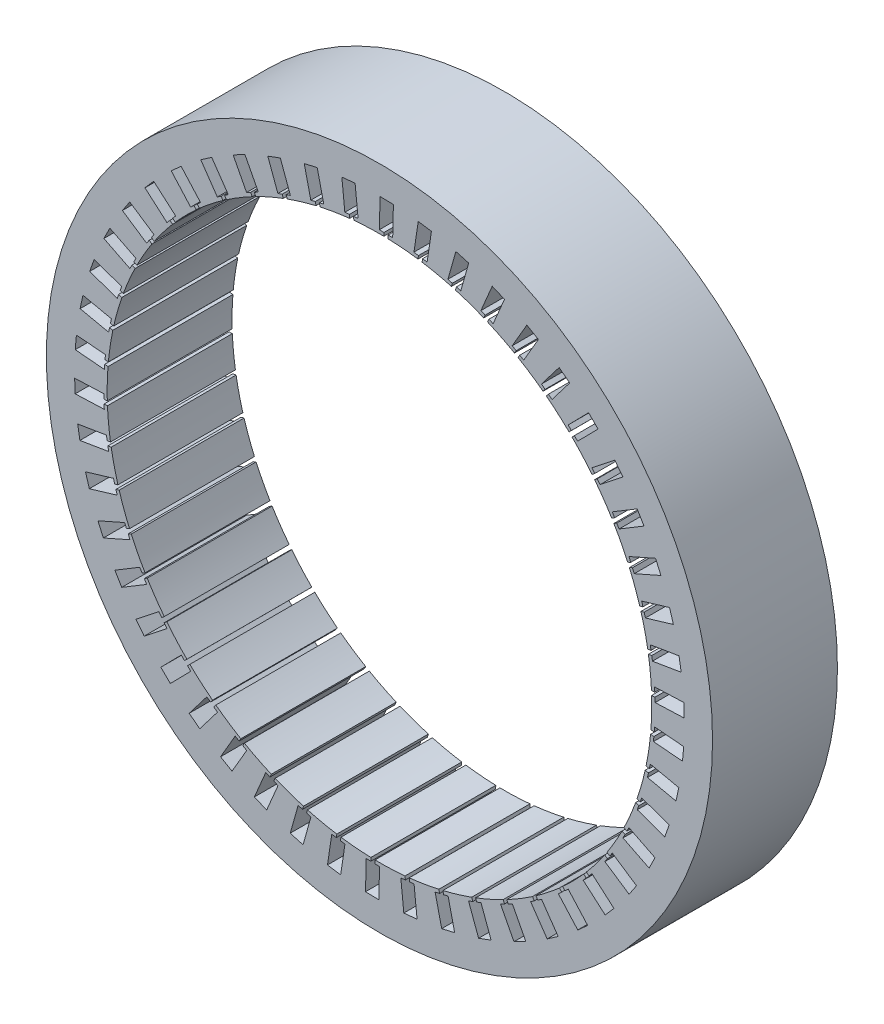
SolidWorks part; units mm, degrees
ref_plane "Спереди" through (0, 0, 0) normal (0, 0, 1) x (1, 0, 0)
ref_plane "Сверху" through (0, 0, 0) normal (0, 1, 0) x (1, 0, 0)
ref_plane "Справа" through (0, 0, 0) normal (1, 0, 0) x (0, 0, -1)
sketch "Эскиз1" plane through (0, 0, 0) normal (0, 0, 1) x (1, 0, 0)
  circle A0 centre (0, 0) radius 80
  circle A1 centre (0, 0) radius 65.4
extrude "Rotor_stack" add sketch "Эскиз1" along normal blind 30 from offset 15
sketch "Эскиз2" plane through (0, 0, 0) normal (0, 0, 1) x (1, 0, 0)
  line L0 (64.5685, 2.0162) -> (66.1692, 2.0786)
  line L1 (66.1692, 2.0786) -> (66.2121, 0.9794)
  line L2 (66.2121, 0.9794) -> (73.2068, 1.2521)
  line L3 (73.2068, 1.2521) -> (73.0822, 4.4496)
  line L4 (73.0822, 4.4496) -> (66.0875, 4.177)
  line L5 (66.0875, 4.177) -> (66.1303, 3.0778)
  line L6 (66.1303, 3.0778) -> (64.5296, 3.0155)
  line L7 (64.5296, 3.0155) -> (64.5685, 2.0162)
  line L8 (63.8067, 10.0929) -> (65.387, 10.3554)
  line L9 (65.387, 10.3554) -> (65.5672, 9.2703)
  line L10 (65.5672, 9.2703) -> (72.4726, 10.4174)
  line L11 (72.4726, 10.4174) -> (71.9482, 13.5742)
  line L12 (71.9482, 13.5742) -> (65.0428, 12.427)
  line L13 (65.0428, 12.427) -> (65.2231, 11.3419)
  line L14 (65.2231, 11.3419) -> (63.6428, 11.0794)
  line L15 (63.6428, 11.0794) -> (63.8067, 10.0929)
  line L16 (62.0386, 18.0104) -> (63.5735, 18.4689)
  line L17 (63.5735, 18.4689) -> (63.8883, 17.4149)
  line L18 (63.8883, 17.4149) -> (70.5955, 19.4185)
  line L19 (70.5955, 19.4185) -> (69.6796, 22.4846)
  line L20 (69.6796, 22.4846) -> (62.9724, 20.4811)
  line L21 (62.9724, 20.4811) -> (63.2873, 19.4271)
  line L22 (63.2873, 19.4271) -> (61.7524, 18.9686)
  line L23 (61.7524, 18.9686) -> (62.0386, 18.0104)
  line L24 (59.2921, 25.6439) -> (60.7574, 26.2912)
  line L25 (60.7574, 26.2912) -> (61.2019, 25.2849)
  line L26 (61.2019, 25.2849) -> (67.605, 28.1133)
  line L27 (67.605, 28.1133) -> (66.312, 31.0405)
  line L28 (66.312, 31.0405) -> (59.9089, 28.2121)
  line L29 (59.9089, 28.2121) -> (60.3534, 27.2059)
  line L30 (60.3534, 27.2059) -> (58.888, 26.5586)
  line L31 (58.888, 26.5586) -> (59.2921, 25.6439)
  line L32 (55.6105, 32.8729) -> (56.9832, 33.6988)
  line L33 (56.9832, 33.6988) -> (57.5503, 32.7562)
  line L34 (57.5503, 32.7562) -> (63.5484, 36.3648)
  line L35 (63.5484, 36.3648) -> (61.8988, 39.1068)
  line L36 (61.8988, 39.1068) -> (55.9006, 35.4982)
  line L37 (55.9006, 35.4982) -> (56.4677, 34.5556)
  line L38 (56.4677, 34.5556) -> (55.095, 33.7298)
  line L39 (55.095, 33.7298) -> (55.6105, 32.8729)
  line L40 (51.0519, 39.5836) -> (52.3103, 40.5749)
  line L41 (52.3103, 40.5749) -> (52.991, 39.7109)
  line L42 (52.991, 39.7109) -> (58.4896, 44.0428)
  line L43 (58.4896, 44.0428) -> (56.5093, 46.5564)
  line L44 (56.5093, 46.5564) -> (51.0107, 42.2245)
  line L45 (51.0107, 42.2245) -> (51.6914, 41.3604)
  line L46 (51.6914, 41.3604) -> (50.4331, 40.3691)
  line L47 (50.4331, 40.3691) -> (51.0519, 39.5836)
  line L48 (45.6882, 45.67) -> (46.8124, 46.8112)
  line L49 (46.8124, 46.8112) -> (47.5961, 46.0393)
  line L50 (47.5961, 46.0393) -> (52.5084, 51.0262)
  line L51 (52.5084, 51.0262) -> (50.2286, 53.2718)
  line L52 (50.2286, 53.2718) -> (45.3163, 48.2849)
  line L53 (45.3163, 48.2849) -> (46.1, 47.513)
  line L54 (46.1, 47.513) -> (44.9758, 46.3717)
  line L55 (44.9758, 46.3717) -> (45.6882, 45.67)
  line L56 (39.604, 51.0361) -> (40.5763, 52.3092)
  line L57 (40.5763, 52.3092) -> (41.4505, 51.6416)
  line L58 (41.4505, 51.6416) -> (45.699, 57.2049)
  line L59 (45.699, 57.2049) -> (43.1558, 59.1471)
  line L60 (43.1558, 59.1471) -> (38.9073, 53.5838)
  line L61 (38.9073, 53.5838) -> (39.7815, 52.9162)
  line L62 (39.7815, 52.9162) -> (38.8093, 51.643)
  line L63 (38.8093, 51.643) -> (39.604, 51.0361)
  line L64 (32.8952, 55.5974) -> (33.7002, 56.9823)
  line L65 (33.7002, 56.9823) -> (34.6512, 56.4295)
  line L66 (34.6512, 56.4295) -> (38.169, 62.4814)
  line L67 (38.169, 62.4814) -> (35.4024, 64.0895)
  line L68 (35.4024, 64.0895) -> (31.8847, 58.0376)
  line L69 (31.8847, 58.0376) -> (32.8357, 57.4848)
  line L70 (32.8357, 57.4848) -> (32.0307, 56.0999)
  line L71 (32.0307, 56.0999) -> (32.8952, 55.5974)
  line L72 (25.6676, 59.2818) -> (26.2927, 60.7567)
  line L73 (26.2927, 60.7567) -> (27.3055, 60.3275)
  line L74 (27.3055, 60.3275) -> (30.037, 66.7726)
  line L75 (30.037, 66.7726) -> (27.0907, 68.0213)
  line L76 (27.0907, 68.0213) -> (24.3592, 61.5762)
  line L77 (24.3592, 61.5762) -> (25.372, 61.147)
  line L78 (25.372, 61.147) -> (24.7469, 59.672)
  line L79 (24.7469, 59.672) -> (25.6676, 59.2818)
  line L80 (18.0352, 62.0314) -> (18.4706, 63.573)
  line L81 (18.4706, 63.573) -> (19.5292, 63.2741)
  line L82 (19.5292, 63.2741) -> (21.4314, 70.0107)
  line L83 (21.4314, 70.0107) -> (18.3518, 70.8803)
  line L84 (18.3518, 70.8803) -> (16.4496, 64.1437)
  line L85 (16.4496, 64.1437) -> (17.5082, 63.8448)
  line L86 (17.5082, 63.8448) -> (17.0729, 62.3031)
  line L87 (17.0729, 62.3031) -> (18.0352, 62.0314)
  line L88 (10.1184, 63.8026) -> (10.3571, 65.3867)
  line L89 (10.3571, 65.3867) -> (11.4448, 65.2228)
  line L90 (11.4448, 65.2228) -> (12.4877, 72.1447)
  line L91 (12.4877, 72.1447) -> (9.3234, 72.6214)
  line L92 (9.3234, 72.6214) -> (8.2805, 65.6996)
  line L93 (8.2805, 65.6996) -> (9.3683, 65.5357)
  line L94 (9.3683, 65.5357) -> (9.1296, 63.9516)
  line L95 (9.1296, 63.9516) -> (10.1184, 63.8026)
  line L96 (2.0421, 64.5677) -> (2.0803, 66.1692)
  line L97 (2.0803, 66.1692) -> (3.18, 66.1429)
  line L98 (3.18, 66.1429) -> (3.3471, 73.1409)
  line L99 (3.3471, 73.1409) -> (0.148, 73.2173)
  line L100 (0.148, 73.2173) -> (-0.0191, 66.2193)
  line L101 (-0.0191, 66.2193) -> (1.0806, 66.1931)
  line L102 (1.0806, 66.1931) -> (1.0423, 64.5916)
  line L103 (1.0423, 64.5916) -> (2.0421, 64.5677)
  line L104 (-6.0665, 64.3145) -> (-6.2293, 65.9082)
  line L105 (-6.2293, 65.9082) -> (-5.135, 66.0199)
  line L106 (-5.135, 66.0199) -> (-5.8463, 72.9837)
  line L107 (-5.8463, 72.9837) -> (-9.0297, 72.6585)
  line L108 (-9.0297, 72.6585) -> (-8.3184, 65.6948)
  line L109 (-8.3184, 65.6948) -> (-7.2241, 65.8066)
  line L110 (-7.2241, 65.8066) -> (-7.0613, 64.2129)
  line L111 (-7.0613, 64.2129) -> (-6.0665, 64.3145)
  line L112 (-14.0794, 63.047) -> (-14.4407, 64.6077)
  line L113 (-14.4407, 64.6077) -> (-13.369, 64.8558)
  line L114 (-13.369, 64.8558) -> (-14.9475, 71.6755)
  line L115 (-14.9475, 71.6755) -> (-18.065, 70.9539)
  line L116 (-18.065, 70.9539) -> (-16.4866, 64.1342)
  line L117 (-16.4866, 64.1342) -> (-15.4149, 64.3822)
  line L118 (-15.4149, 64.3822) -> (-15.0537, 62.8215)
  line L119 (-15.0537, 62.8215) -> (-14.0794, 63.047)
  line L120 (-21.8703, 60.7853) -> (-22.4243, 62.2884)
  line L121 (-22.4243, 62.2884) -> (-21.3922, 62.6688)
  line L122 (-21.3922, 62.6688) -> (-23.8129, 69.2369)
  line L123 (-23.8129, 69.2369) -> (-26.8155, 68.1302)
  line L124 (-26.8155, 68.1302) -> (-24.3947, 61.5621)
  line L125 (-24.3947, 61.5621) -> (-23.3626, 61.9426)
  line L126 (-23.3626, 61.9426) -> (-22.8086, 60.4395)
  line L127 (-22.8086, 60.4395) -> (-21.8703, 60.7853)
  line L128 (-29.3163, 57.5649) -> (-30.0543, 58.9867)
  line L129 (-30.0543, 58.9867) -> (-29.078, 59.4935)
  line L130 (-29.078, 59.4935) -> (-32.3028, 65.7064)
  line L131 (-32.3028, 65.7064) -> (-35.143, 64.2321)
  line L132 (-35.143, 64.2321) -> (-31.9181, 58.0192)
  line L133 (-31.9181, 58.0192) -> (-30.9418, 58.526)
  line L134 (-30.9418, 58.526) -> (-30.2038, 57.1042)
  line L135 (-30.2038, 57.1042) -> (-29.3163, 57.5649)
  line L136 (-36.2999, 53.4367) -> (-37.2103, 54.7548)
  line L137 (-37.2103, 54.7548) -> (-36.3052, 55.3799)
  line L138 (-36.3052, 55.3799) -> (-40.2833, 61.1396)
  line L139 (-40.2833, 61.1396) -> (-42.9163, 59.3211)
  line L140 (-42.9163, 59.3211) -> (-38.9382, 53.5613)
  line L141 (-38.9382, 53.5613) -> (-38.0331, 54.1865)
  line L142 (-38.0331, 54.1865) -> (-37.1227, 52.8684)
  line L143 (-37.1227, 52.8684) -> (-36.2999, 53.4367)
  line L144 (-42.711, 48.4657) -> (-43.7795, 49.6593)
  line L145 (-43.7795, 49.6593) -> (-42.9598, 50.393)
  line L146 (-42.9598, 50.393) -> (-47.6285, 55.6087)
  line L147 (-47.6285, 55.6087) -> (-50.0128, 53.4745)
  line L148 (-50.0128, 53.4745) -> (-45.3442, 48.2587)
  line L149 (-45.3442, 48.2587) -> (-44.5246, 48.9924)
  line L150 (-44.5246, 48.9924) -> (-43.4561, 47.7988)
  line L151 (-43.4561, 47.7988) -> (-42.711, 48.4657)
  line L152 (-48.4486, 42.7304) -> (-49.6582, 43.7807)
  line L153 (-49.6582, 43.7807) -> (-48.937, 44.6113)
  line L154 (-48.937, 44.6113) -> (-54.2225, 49.2008)
  line L155 (-54.2225, 49.2008) -> (-56.3206, 46.7845)
  line L156 (-56.3206, 46.7845) -> (-51.035, 42.1951)
  line L157 (-51.035, 42.1951) -> (-50.3138, 43.0257)
  line L158 (-50.3138, 43.0257) -> (-49.1043, 41.9754)
  line L159 (-49.1043, 41.9754) -> (-48.4486, 42.7304)
  line L160 (-53.4221, 36.3213) -> (-54.7538, 37.2117)
  line L161 (-54.7538, 37.2117) -> (-54.1424, 38.1261)
  line L162 (-54.1424, 38.1261) -> (-59.9615, 42.0169)
  line L163 (-59.9615, 42.0169) -> (-61.7401, 39.3568)
  line L164 (-61.7401, 39.3568) -> (-55.9211, 35.466)
  line L165 (-55.9211, 35.466) -> (-55.3096, 36.3804)
  line L166 (-55.3096, 36.3804) -> (-53.978, 35.49)
  line L167 (-53.978, 35.49) -> (-53.4221, 36.3213)
  line L168 (-57.5531, 29.3393) -> (-58.9859, 30.0558)
  line L169 (-58.9859, 30.0558) -> (-58.4939, 31.0396)
  line L170 (-58.4939, 31.0396) -> (-64.7548, 34.1705)
  line L171 (-64.7548, 34.1705) -> (-66.186, 31.3084)
  line L172 (-66.186, 31.3084) -> (-59.9252, 28.1775)
  line L173 (-59.9252, 28.1775) -> (-59.4332, 29.1614)
  line L174 (-59.4332, 29.1614) -> (-58.0004, 28.4449)
  line L175 (-58.0004, 28.4449) -> (-57.5531, 29.3393)
  line L176 (-60.7765, 21.8946) -> (-62.2878, 22.4259)
  line L177 (-62.2878, 22.4259) -> (-61.923, 23.4636)
  line L178 (-61.923, 23.4636) -> (-68.5269, 25.7851)
  line L179 (-68.5269, 25.7851) -> (-69.5881, 22.7662)
  line L180 (-69.5881, 22.7662) -> (-62.9842, 20.4447)
  line L181 (-62.9842, 20.4447) -> (-62.6194, 21.4825)
  line L182 (-62.6194, 21.4825) -> (-61.1082, 20.9512)
  line L183 (-61.1082, 20.9512) -> (-60.7765, 21.8946)
  line L184 (-63.0414, 14.1047) -> (-64.6073, 14.4423)
  line L185 (-64.6073, 14.4423) -> (-64.3755, 15.5176)
  line L186 (-64.3755, 15.5176) -> (-71.2182, 16.9931)
  line L187 (-71.2182, 16.9931) -> (-71.8927, 13.865)
  line L188 (-71.8927, 13.865) -> (-65.05, 12.3895)
  line L189 (-65.05, 12.3895) -> (-64.8181, 13.4648)
  line L190 (-64.8181, 13.4648) -> (-63.2522, 13.1271)
  line L191 (-63.2522, 13.1271) -> (-63.0414, 14.1047)
  line L192 (-64.3121, 6.0923) -> (-65.908, 6.231)
  line L193 (-65.908, 6.231) -> (-65.8127, 7.3269)
  line L194 (-65.8127, 7.3269) -> (-72.7864, 7.9331)
  line L195 (-72.7864, 7.9331) -> (-73.0636, 4.7451)
  line L196 (-73.0636, 4.7451) -> (-66.0899, 4.1389)
  line L197 (-66.0899, 4.1389) -> (-65.9946, 5.2348)
  line L198 (-65.9946, 5.2348) -> (-64.3987, 5.096)
  line L199 (-64.3987, 5.096) -> (-64.3121, 6.0923)
  line L200 (-64.5685, -2.0162) -> (-66.1692, -2.0786)
  line L201 (-66.1692, -2.0786) -> (-66.2121, -0.9794)
  line L202 (-66.2121, -0.9794) -> (-73.2068, -1.2521)
  line L203 (-73.2068, -1.2521) -> (-73.0822, -4.4496)
  line L204 (-73.0822, -4.4496) -> (-66.0875, -4.177)
  line L205 (-66.0875, -4.177) -> (-66.1303, -3.0778)
  line L206 (-66.1303, -3.0778) -> (-64.5296, -3.0155)
  line L207 (-64.5296, -3.0155) -> (-64.5685, -2.0162)
  line L208 (-63.8067, -10.0929) -> (-65.387, -10.3554)
  line L209 (-65.387, -10.3554) -> (-65.5672, -9.2703)
  line L210 (-65.5672, -9.2703) -> (-72.4726, -10.4174)
  line L211 (-72.4726, -10.4174) -> (-71.9482, -13.5742)
  line L212 (-71.9482, -13.5742) -> (-65.0428, -12.427)
  line L213 (-65.0428, -12.427) -> (-65.2231, -11.3419)
  line L214 (-65.2231, -11.3419) -> (-63.6428, -11.0794)
  line L215 (-63.6428, -11.0794) -> (-63.8067, -10.0929)
  line L216 (-62.0386, -18.0104) -> (-63.5735, -18.4689)
  line L217 (-63.5735, -18.4689) -> (-63.8883, -17.4149)
  line L218 (-63.8883, -17.4149) -> (-70.5955, -19.4185)
  line L219 (-70.5955, -19.4185) -> (-69.6796, -22.4846)
  line L220 (-69.6796, -22.4846) -> (-62.9724, -20.4811)
  line L221 (-62.9724, -20.4811) -> (-63.2873, -19.4271)
  line L222 (-63.2873, -19.4271) -> (-61.7524, -18.9686)
  line L223 (-61.7524, -18.9686) -> (-62.0386, -18.0104)
  line L224 (-59.2921, -25.6439) -> (-60.7574, -26.2912)
  line L225 (-60.7574, -26.2912) -> (-61.2019, -25.2849)
  line L226 (-61.2019, -25.2849) -> (-67.605, -28.1133)
  line L227 (-67.605, -28.1133) -> (-66.312, -31.0405)
  line L228 (-66.312, -31.0405) -> (-59.9089, -28.2121)
  line L229 (-59.9089, -28.2121) -> (-60.3534, -27.2059)
  line L230 (-60.3534, -27.2059) -> (-58.888, -26.5586)
  line L231 (-58.888, -26.5586) -> (-59.2921, -25.6439)
  line L232 (-55.6105, -32.8729) -> (-56.9832, -33.6988)
  line L233 (-56.9832, -33.6988) -> (-57.5503, -32.7562)
  line L234 (-57.5503, -32.7562) -> (-63.5484, -36.3648)
  line L235 (-63.5484, -36.3648) -> (-61.8988, -39.1068)
  line L236 (-61.8988, -39.1068) -> (-55.9006, -35.4982)
  line L237 (-55.9006, -35.4982) -> (-56.4677, -34.5556)
  line L238 (-56.4677, -34.5556) -> (-55.095, -33.7298)
  line L239 (-55.095, -33.7298) -> (-55.6105, -32.8729)
  line L240 (-51.0519, -39.5836) -> (-52.3103, -40.5749)
  line L241 (-52.3103, -40.5749) -> (-52.991, -39.7109)
  line L242 (-52.991, -39.7109) -> (-58.4896, -44.0428)
  line L243 (-58.4896, -44.0428) -> (-56.5093, -46.5564)
  line L244 (-56.5093, -46.5564) -> (-51.0107, -42.2245)
  line L245 (-51.0107, -42.2245) -> (-51.6914, -41.3604)
  line L246 (-51.6914, -41.3604) -> (-50.4331, -40.3691)
  line L247 (-50.4331, -40.3691) -> (-51.0519, -39.5836)
  line L248 (-45.6882, -45.67) -> (-46.8124, -46.8112)
  line L249 (-46.8124, -46.8112) -> (-47.5961, -46.0393)
  line L250 (-47.5961, -46.0393) -> (-52.5084, -51.0262)
  line L251 (-52.5084, -51.0262) -> (-50.2286, -53.2718)
  line L252 (-50.2286, -53.2718) -> (-45.3163, -48.2849)
  line L253 (-45.3163, -48.2849) -> (-46.1, -47.513)
  line L254 (-46.1, -47.513) -> (-44.9758, -46.3717)
  line L255 (-44.9758, -46.3717) -> (-45.6882, -45.67)
  line L256 (-39.604, -51.0361) -> (-40.5763, -52.3092)
  line L257 (-40.5763, -52.3092) -> (-41.4505, -51.6416)
  line L258 (-41.4505, -51.6416) -> (-45.699, -57.2049)
  line L259 (-45.699, -57.2049) -> (-43.1558, -59.1471)
  line L260 (-43.1558, -59.1471) -> (-38.9073, -53.5838)
  line L261 (-38.9073, -53.5838) -> (-39.7815, -52.9162)
  line L262 (-39.7815, -52.9162) -> (-38.8093, -51.643)
  line L263 (-38.8093, -51.643) -> (-39.604, -51.0361)
  line L264 (-32.8952, -55.5974) -> (-33.7002, -56.9823)
  line L265 (-33.7002, -56.9823) -> (-34.6512, -56.4295)
  line L266 (-34.6512, -56.4295) -> (-38.169, -62.4814)
  line L267 (-38.169, -62.4814) -> (-35.4024, -64.0895)
  line L268 (-35.4024, -64.0895) -> (-31.8847, -58.0376)
  line L269 (-31.8847, -58.0376) -> (-32.8357, -57.4848)
  line L270 (-32.8357, -57.4848) -> (-32.0307, -56.0999)
  line L271 (-32.0307, -56.0999) -> (-32.8952, -55.5974)
  line L272 (-25.6676, -59.2818) -> (-26.2927, -60.7567)
  line L273 (-26.2927, -60.7567) -> (-27.3055, -60.3275)
  line L274 (-27.3055, -60.3275) -> (-30.037, -66.7726)
  line L275 (-30.037, -66.7726) -> (-27.0907, -68.0213)
  line L276 (-27.0907, -68.0213) -> (-24.3592, -61.5762)
  line L277 (-24.3592, -61.5762) -> (-25.372, -61.147)
  line L278 (-25.372, -61.147) -> (-24.7469, -59.672)
  line L279 (-24.7469, -59.672) -> (-25.6676, -59.2818)
  line L280 (-18.0352, -62.0314) -> (-18.4706, -63.573)
  line L281 (-18.4706, -63.573) -> (-19.5292, -63.2741)
  line L282 (-19.5292, -63.2741) -> (-21.4314, -70.0107)
  line L283 (-21.4314, -70.0107) -> (-18.3518, -70.8803)
  line L284 (-18.3518, -70.8803) -> (-16.4496, -64.1437)
  line L285 (-16.4496, -64.1437) -> (-17.5082, -63.8448)
  line L286 (-17.5082, -63.8448) -> (-17.0729, -62.3031)
  line L287 (-17.0729, -62.3031) -> (-18.0352, -62.0314)
  line L288 (-10.1184, -63.8026) -> (-10.3571, -65.3867)
  line L289 (-10.3571, -65.3867) -> (-11.4448, -65.2228)
  line L290 (-11.4448, -65.2228) -> (-12.4877, -72.1447)
  line L291 (-12.4877, -72.1447) -> (-9.3234, -72.6214)
  line L292 (-9.3234, -72.6214) -> (-8.2805, -65.6996)
  line L293 (-8.2805, -65.6996) -> (-9.3683, -65.5357)
  line L294 (-9.3683, -65.5357) -> (-9.1296, -63.9516)
  line L295 (-9.1296, -63.9516) -> (-10.1184, -63.8026)
  line L296 (-2.0421, -64.5677) -> (-2.0803, -66.1692)
  line L297 (-2.0803, -66.1692) -> (-3.18, -66.1429)
  line L298 (-3.18, -66.1429) -> (-3.3471, -73.1409)
  line L299 (-3.3471, -73.1409) -> (-0.148, -73.2173)
  line L300 (-0.148, -73.2173) -> (0.0191, -66.2193)
  line L301 (0.0191, -66.2193) -> (-1.0806, -66.1931)
  line L302 (-1.0806, -66.1931) -> (-1.0423, -64.5916)
  line L303 (-1.0423, -64.5916) -> (-2.0421, -64.5677)
  line L304 (6.0665, -64.3145) -> (6.2293, -65.9082)
  line L305 (6.2293, -65.9082) -> (5.135, -66.0199)
  line L306 (5.135, -66.0199) -> (5.8463, -72.9837)
  line L307 (5.8463, -72.9837) -> (9.0297, -72.6585)
  line L308 (9.0297, -72.6585) -> (8.3184, -65.6948)
  line L309 (8.3184, -65.6948) -> (7.2241, -65.8066)
  line L310 (7.2241, -65.8066) -> (7.0613, -64.2129)
  line L311 (7.0613, -64.2129) -> (6.0665, -64.3145)
  line L312 (14.0794, -63.047) -> (14.4407, -64.6077)
  line L313 (14.4407, -64.6077) -> (13.369, -64.8558)
  line L314 (13.369, -64.8558) -> (14.9475, -71.6755)
  line L315 (14.9475, -71.6755) -> (18.065, -70.9539)
  line L316 (18.065, -70.9539) -> (16.4866, -64.1342)
  line L317 (16.4866, -64.1342) -> (15.4149, -64.3822)
  line L318 (15.4149, -64.3822) -> (15.0537, -62.8215)
  line L319 (15.0537, -62.8215) -> (14.0794, -63.047)
  line L320 (21.8703, -60.7853) -> (22.4243, -62.2884)
  line L321 (22.4243, -62.2884) -> (21.3922, -62.6688)
  line L322 (21.3922, -62.6688) -> (23.8129, -69.2369)
  line L323 (23.8129, -69.2369) -> (26.8155, -68.1302)
  line L324 (26.8155, -68.1302) -> (24.3947, -61.5621)
  line L325 (24.3947, -61.5621) -> (23.3626, -61.9426)
  line L326 (23.3626, -61.9426) -> (22.8086, -60.4395)
  line L327 (22.8086, -60.4395) -> (21.8703, -60.7853)
  line L328 (29.3163, -57.5649) -> (30.0543, -58.9867)
  line L329 (30.0543, -58.9867) -> (29.078, -59.4935)
  line L330 (29.078, -59.4935) -> (32.3028, -65.7064)
  line L331 (32.3028, -65.7064) -> (35.143, -64.2321)
  line L332 (35.143, -64.2321) -> (31.9181, -58.0192)
  line L333 (31.9181, -58.0192) -> (30.9418, -58.526)
  line L334 (30.9418, -58.526) -> (30.2038, -57.1042)
  line L335 (30.2038, -57.1042) -> (29.3163, -57.5649)
  line L336 (36.2999, -53.4367) -> (37.2103, -54.7548)
  line L337 (37.2103, -54.7548) -> (36.3052, -55.3799)
  line L338 (36.3052, -55.3799) -> (40.2833, -61.1396)
  line L339 (40.2833, -61.1396) -> (42.9163, -59.3211)
  line L340 (42.9163, -59.3211) -> (38.9382, -53.5613)
  line L341 (38.9382, -53.5613) -> (38.0331, -54.1865)
  line L342 (38.0331, -54.1865) -> (37.1227, -52.8684)
  line L343 (37.1227, -52.8684) -> (36.2999, -53.4367)
  line L344 (42.711, -48.4657) -> (43.7795, -49.6593)
  line L345 (43.7795, -49.6593) -> (42.9598, -50.393)
  line L346 (42.9598, -50.393) -> (47.6285, -55.6087)
  line L347 (47.6285, -55.6087) -> (50.0128, -53.4745)
  line L348 (50.0128, -53.4745) -> (45.3442, -48.2587)
  line L349 (45.3442, -48.2587) -> (44.5246, -48.9924)
  line L350 (44.5246, -48.9924) -> (43.4561, -47.7988)
  line L351 (43.4561, -47.7988) -> (42.711, -48.4657)
  line L352 (48.4486, -42.7304) -> (49.6582, -43.7807)
  line L353 (49.6582, -43.7807) -> (48.937, -44.6113)
  line L354 (48.937, -44.6113) -> (54.2225, -49.2008)
  line L355 (54.2225, -49.2008) -> (56.3206, -46.7845)
  line L356 (56.3206, -46.7845) -> (51.035, -42.1951)
  line L357 (51.035, -42.1951) -> (50.3138, -43.0257)
  line L358 (50.3138, -43.0257) -> (49.1043, -41.9754)
  line L359 (49.1043, -41.9754) -> (48.4486, -42.7304)
  line L360 (53.4221, -36.3213) -> (54.7538, -37.2117)
  line L361 (54.7538, -37.2117) -> (54.1424, -38.1261)
  line L362 (54.1424, -38.1261) -> (59.9615, -42.0169)
  line L363 (59.9615, -42.0169) -> (61.7401, -39.3568)
  line L364 (61.7401, -39.3568) -> (55.9211, -35.466)
  line L365 (55.9211, -35.466) -> (55.3096, -36.3804)
  line L366 (55.3096, -36.3804) -> (53.978, -35.49)
  line L367 (53.978, -35.49) -> (53.4221, -36.3213)
  line L368 (57.5531, -29.3393) -> (58.9859, -30.0558)
  line L369 (58.9859, -30.0558) -> (58.4939, -31.0396)
  line L370 (58.4939, -31.0396) -> (64.7548, -34.1705)
  line L371 (64.7548, -34.1705) -> (66.186, -31.3084)
  line L372 (66.186, -31.3084) -> (59.9252, -28.1775)
  line L373 (59.9252, -28.1775) -> (59.4332, -29.1614)
  line L374 (59.4332, -29.1614) -> (58.0004, -28.4449)
  line L375 (58.0004, -28.4449) -> (57.5531, -29.3393)
  line L376 (60.7765, -21.8946) -> (62.2878, -22.4259)
  line L377 (62.2878, -22.4259) -> (61.923, -23.4636)
  line L378 (61.923, -23.4636) -> (68.5269, -25.7851)
  line L379 (68.5269, -25.7851) -> (69.5881, -22.7662)
  line L380 (69.5881, -22.7662) -> (62.9842, -20.4447)
  line L381 (62.9842, -20.4447) -> (62.6194, -21.4825)
  line L382 (62.6194, -21.4825) -> (61.1082, -20.9512)
  line L383 (61.1082, -20.9512) -> (60.7765, -21.8946)
  line L384 (63.0414, -14.1047) -> (64.6073, -14.4423)
  line L385 (64.6073, -14.4423) -> (64.3755, -15.5176)
  line L386 (64.3755, -15.5176) -> (71.2182, -16.9931)
  line L387 (71.2182, -16.9931) -> (71.8927, -13.865)
  line L388 (71.8927, -13.865) -> (65.05, -12.3895)
  line L389 (65.05, -12.3895) -> (64.8181, -13.4648)
  line L390 (64.8181, -13.4648) -> (63.2522, -13.1271)
  line L391 (63.2522, -13.1271) -> (63.0414, -14.1047)
  line L392 (64.3121, -6.0923) -> (65.908, -6.231)
  line L393 (65.908, -6.231) -> (65.8127, -7.3269)
  line L394 (65.8127, -7.3269) -> (72.7864, -7.9331)
  line L395 (72.7864, -7.9331) -> (73.0636, -4.7451)
  line L396 (73.0636, -4.7451) -> (66.0899, -4.1389)
  line L397 (66.0899, -4.1389) -> (65.9946, -5.2348)
  line L398 (65.9946, -5.2348) -> (64.3987, -5.096)
  line L399 (64.3987, -5.096) -> (64.3121, -6.0923)
extrude "Rotor_50_slots" cut sketch "Эскиз2" against normal mid plane 32
